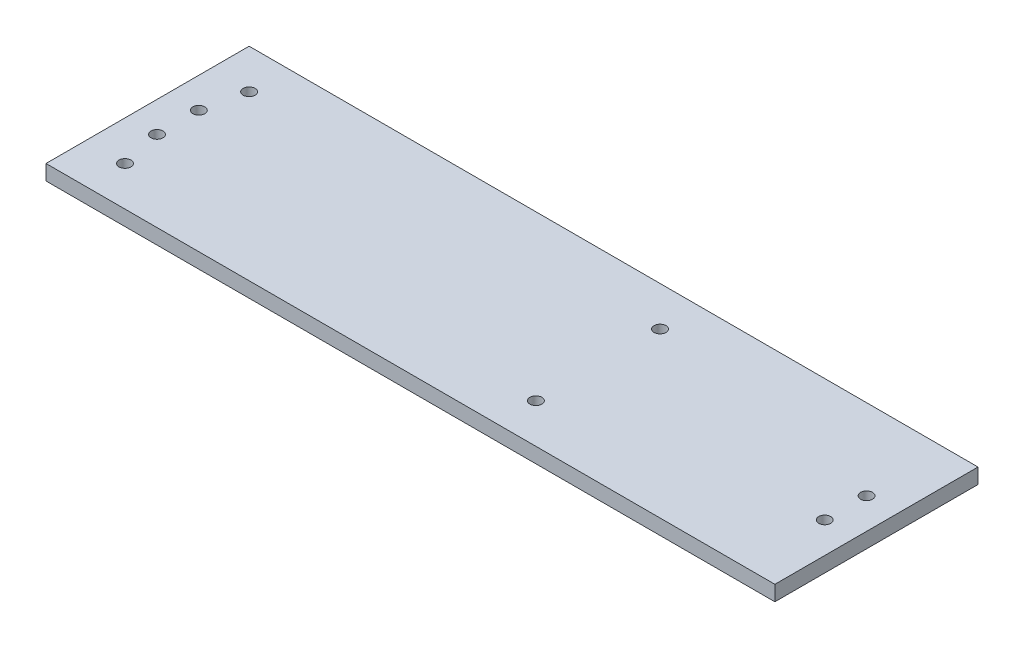
SolidWorks part; units mm, degrees
material "6061-T6 (SS)"
ref_plane "Front" through (0, 0, 0) normal (0, 0, 1) x (1, 0, 0)
ref_plane "Top" through (0, 0, 0) normal (0, 1, 0) x (1, 0, 0)
ref_plane "Right" through (0, 0, 0) normal (1, 0, 0) x (0, 0, -1)
sketch "Sketch1" plane through (0, 0, 0) normal (0, 1, 0) x (1, 0, 0)
  line L1 (-152.5, -42.5) -> (152.5, -42.5)
  line L2 (-152.5, -42.5) -> (-152.5, 42.5)
  line L3 (-152.5, 42.5) -> (152.5, 42.5)
  line L4 (152.5, -42.5) -> (152.5, 42.5)
  line L5 (-152.5, -42.5) -> (152.5, 42.5) construction
  line L6 (-152.5, 42.5) -> (152.5, -42.5) construction
  point P0 (0, 0)
  dimension "D1" = 85
  dimension "D2" = 305
extrude "Boss-Extrude1" add sketch "Sketch1" along normal mid plane 6.35
sketch "Sketch4" plane through (-2.5, 0, 0) normal (0, -1, 0) x (-1, 0, 0)
  line L0 (133.48, -13.48) -> (120.98, -13.48) construction
  line L1 (120.98, -13.48) -> (-2.5, -13.48) construction
  line L2 (143.285, -25.98) -> (145.98, -25.98) construction
  line L3 (-2.5, 0) -> (49997.5, 0) construction
  line L4 (120.98, -25.98) -> (123.675, -25.98) construction
  line L5 (133.48, -13.48) -> (133.48, -16.175) construction
  line L6 (120.98, 13.48) -> (120.98, 25.98) construction
  line L7 (120.98, -13.48) -> (120.98, -25.98) construction
  line L8 (133.48, 13.48) -> (133.48, 16.175) construction
  line L9 (120.98, 25.98) -> (123.675, 25.98) construction
  line L10 (143.285, 25.98) -> (145.98, 25.98) construction
  line L11 (120.98, 13.48) -> (-2.5, 13.48) construction
  line L12 (133.48, 13.48) -> (120.98, 13.48) construction
  line L14 (133.48, -35.785) -> (133.48, -38.48) construction
  line L15 (-2.5, 13.48) -> (-2.5, -13.48) construction
  line L16 (150, -42.5) -> (-155, -42.5) construction
  line L17 (150, 42.5) -> (150, -42.5) construction
  circle A1 centre (133.48, -25.98) radius 2.5
  circle A2 centre (133.48, -25.98) radius 12.5 construction
  circle A4 centre (133.48, -25.98) radius 9.805 construction
  circle A5 centre (133.48, 25.98) radius 9.805 construction
  circle A6 centre (133.48, 25.98) radius 12.5 construction
  circle A7 centre (133.48, 25.98) radius 2.5
  dimension "D1" = 25.98
  dimension "D2" = 5
  dimension "D3" = 25
  dimension "D4" = 19.61
  dimension "D5" = 16.52
  dimension "D6" = 16.52
  dimension "D7" = 135.98
extrude "Cut-Extrude2" cut sketch "Sketch4" against normal through all both and the other way through all
ref_plane "Plane1" through (-50, 0, 0) normal (-1, 0, 0) x (0, 0, 1)
mirror "Mirror2" about plane through (-50, 0, 0) normal (-1, 0, 0) of "Cut-Extrude2"
sketch "Sketch6" plane through (0, 3.175, 0) normal (0, 1, 0) x (1, 0, 0)
  line L0 (-146.15, 8.75) -> (-139.8, 8.75) construction
  line L1 (-152.5, 42.5) -> (-152.5, -42.5) construction
  line L4 (-146.15, 8.75) -> (-146.15, -8.75) construction
  line L5 (-146.15, 0) -> (-152.5, 0) construction
  line L6 (-146.15, -8.75) -> (-139.8, -8.75) construction
  circle A0 centre (-139.8, 8.75) radius 2.5
  circle A1 centre (-139.8, -8.75) radius 2.5
  dimension "D2" = 5
  dimension "D1" = 12.7
  dimension "D3" = 17.5
  dimension "D4" = 6.35
extrude "Cut-Extrude3" cut sketch "Sketch6" against normal through all both and the other way through all
sketch "Sketch7" plane through (0, -3.175, 0) normal (0, -1, 0) x (1, 0, 0)
  line L0 (139.6, 8.75) -> (139.6, -8.75) construction
  line L1 (152.5, 0) -> (139.6, 0) construction
  line L2 (152.5, 42.5) -> (152.5, -42.5) construction
  line L3 (-152.5, 42.5) -> (152.5, 42.5) construction
  circle A0 centre (139.6, -8.75) radius 2.5
  circle A1 centre (139.6, 8.75) radius 2.5
  dimension "D1" = 5
  dimension "D2" = 5
  dimension "D3" = 17.5
  dimension "D4" = 42.5
  dimension "D5" = 12.9
extrude "Cut-Extrude4" cut sketch "Sketch7" against normal through all both and the other way through all
